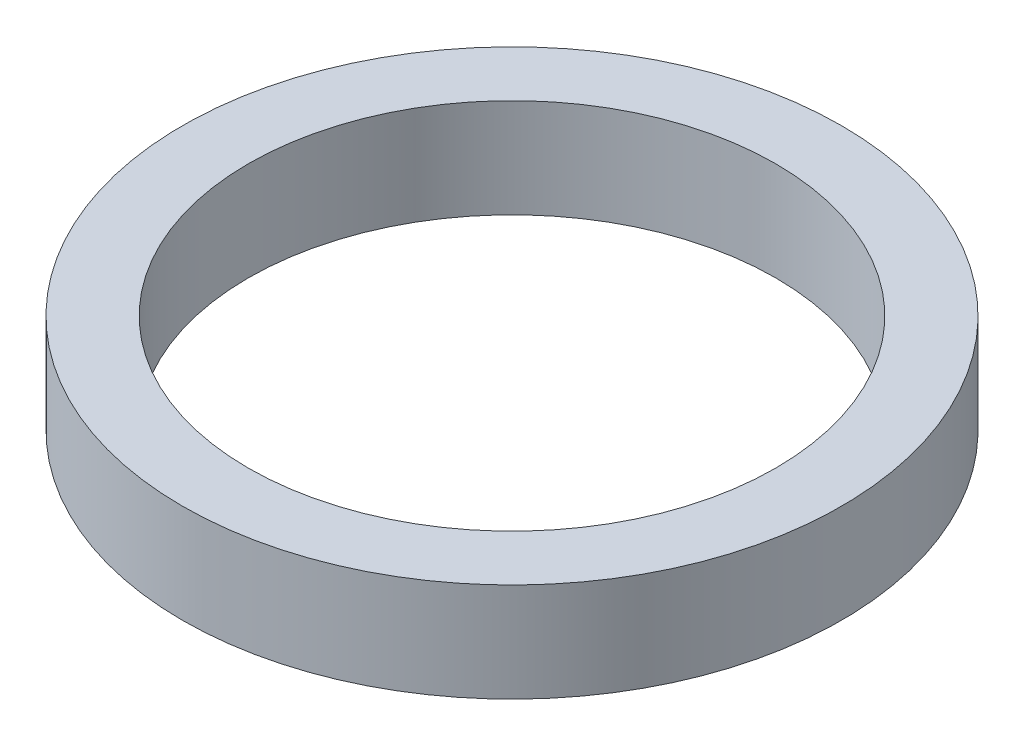
SolidWorks part; units mm, degrees
ref_plane "Front Plane" through (0, 0, 0) normal (0, 0, 1) x (1, 0, 0)
ref_plane "Top Plane" through (0, 0, 0) normal (0, 1, 0) x (1, 0, 0)
ref_plane "Right Plane" through (0, 0, 0) normal (1, 0, 0) x (0, 0, -1)
sketch "Sketch2" plane through (0, 0, 0) normal (0, 1, 0) x (1, 0, 0)
  circle A0 centre (0, 0) radius 4
  circle A1 centre (0, 0) radius 5
  dimension "D1" = 8
  dimension "D2" = 10
extrude "Boss-Extrude1" add sketch "Sketch2" along normal blind 1.5
